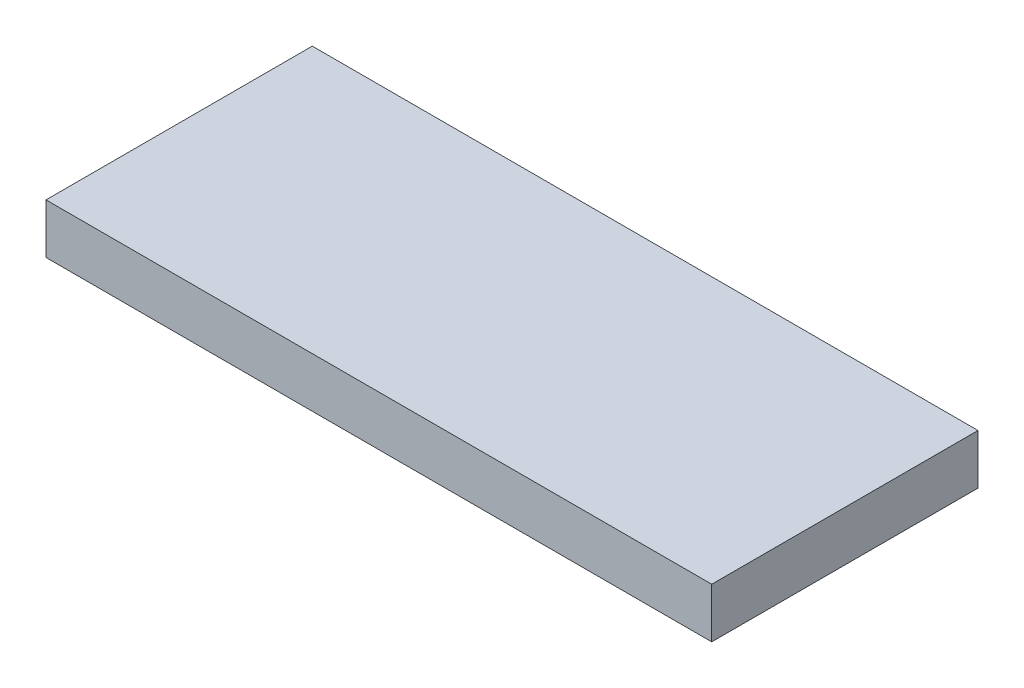
SolidWorks part; units mm, degrees
ref_plane "Front Plane" through (0, 0, 0) normal (0, 0, 1) x (1, 0, 0)
ref_plane "Top Plane" through (0, 0, 0) normal (0, 1, 0) x (1, 0, 0)
ref_plane "Right Plane" through (0, 0, 0) normal (1, 0, 0) x (0, 0, -1)
sketch "Sketch1" plane through (0, 0, 0) normal (0, 1, 0) x (1, 0, 0)
  line L1 (10, -4) -> (-10, -4)
  line L2 (10, -4) -> (10, 4)
  line L3 (10, 4) -> (-10, 4)
  line L4 (-10, -4) -> (-10, 4)
  line L5 (10, -4) -> (-10, 4) construction
  line L6 (10, 4) -> (-10, -4) construction
  point P0 (0, 0)
  dimension "D1" = 20
  dimension "D2" = 8
extrude "Boss-Extrude1" add sketch "Sketch1" along normal blind 1.5
sketch "Sketch2" plane through (0, 1.5, 0) normal (0, 1, 0) x (1, 0, 0)
  line L0 (-3.6611, 0.8116) -> (-6.2483, 1.3852)
  line L5 (-10, -4) -> (10, -4) construction
  line L6 (-5.6337, 3.3487) -> (-6.5211, -0.6541)
  line L7 (-6.5211, -0.6541) -> (-4.2757, -1.1519)
  line L8 (-4.2757, -1.1519) -> (-3.3883, 2.8509)
  line L9 (-3.3883, 2.8509) -> (-5.6337, 3.3487)
  line L10 (-5.6337, 3.3487) -> (-4.2757, -1.1519) construction
  line L11 (-3.3883, 7.7191) -> (-3.3883, -7.8706) construction
  line L12 (-3.3883, -7.8706) -> (-6.5211, -7.8706) construction
  line L13 (-6.5211, -7.8706) -> (-6.5211, 7.7191) construction
  line L14 (-6.5211, 7.7191) -> (-3.3883, 7.7191) construction
  circle A0 centre (0, 0) radius 3.75
  circle A1 centre (0, 0) radius 6.4
  point P10 (-4.9547, 1.0984)
  dimension "D1" = 7.5
  dimension "D2" = 12.8
  dimension "D3" = 12.5
  dimension "D4" = 4.1
  dimension "D5" = 2.3
  dimension "D6" = 3.3883
  dimension "D7" = 6.5211
  dimension "D8" = 3.1329
